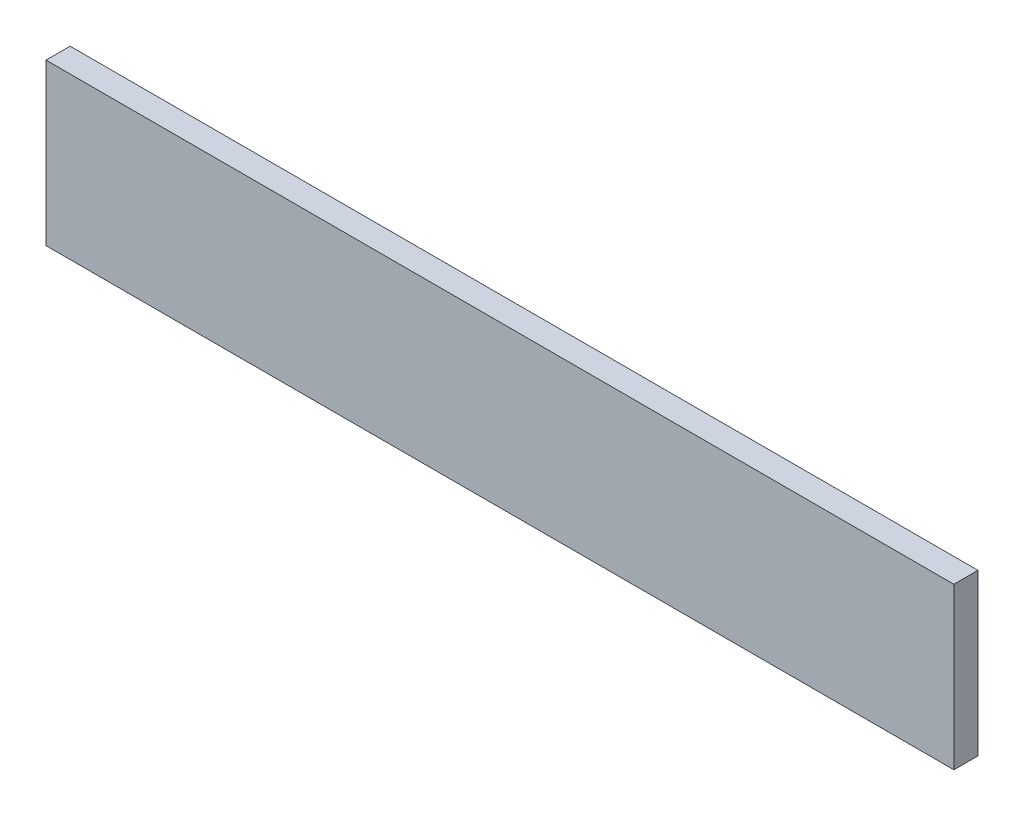
SolidWorks part; units mm, degrees
ref_plane "Front Plane" through (0, 0, 0) normal (0, 0, 1) x (1, 0, 0)
ref_plane "Top Plane" through (0, 0, 0) normal (0, 1, 0) x (1, 0, 0)
ref_plane "Right Plane" through (0, 0, 0) normal (1, 0, 0) x (0, 0, -1)
sketch "Sketch1" plane through (0, 0, 0) normal (0, 0, 1) x (1, 0, 0)
  line L1 (0, 0) -> (717.55, 0)
  line L2 (0, 0) -> (0, 127)
  line L3 (0, 127) -> (717.55, 127)
  line L4 (717.55, 0) -> (717.55, 127)
  point P4 (0, 0)
  dimension "D1" = 127
  dimension "D2" = 717.55
extrude "Boss-Extrude1" add sketch "Sketch1" along normal blind 19.05
